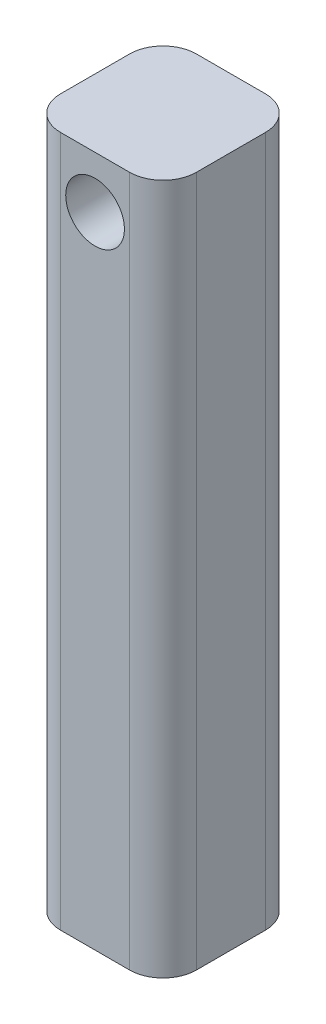
SolidWorks part; units mm, degrees
ref_plane "Front Plane" through (0, 0, 0) normal (0, 0, 1) x (1, 0, 0)
ref_plane "Top Plane" through (0, 0, 0) normal (0, 1, 0) x (1, 0, 0)
ref_plane "Right Plane" through (0, 0, 0) normal (1, 0, 0) x (0, 0, -1)
sketch "Sketch1" plane through (0, 0, 0) normal (0, 1, 0) x (1, 0, 0)
  line L1 (-3, -5.9) -> (3, -5.9)
  line L2 (-5.9, -3) -> (-5.9, 3)
  line L3 (-3, 5.9) -> (3, 5.9)
  line L4 (5.9, -3) -> (5.9, 3)
  line L5 (-5.9, -5.9) -> (5.9, 5.9) construction
  line L6 (-5.9, 5.9) -> (5.9, -5.9) construction
  arc A0 (3, -5.9) -> (5.9, -3) centre (3, -3) ccw
  arc A1 (-3, -5.9) -> (-5.9, -3) centre (-3, -3) cw
  arc A2 (-5.9, 3) -> (-3, 5.9) centre (-3, 3) cw
  arc A3 (3, 5.9) -> (5.9, 3) centre (3, 3) cw
  circle A4 centre (0, 0) radius 2.55
  point P0 (0, 0)
  dimension "D2" = 2.9
  dimension "D3" = 2.9
  dimension "D4" = 5.1
  dimension "D1" = 11.8
extrude "Boss-Extrude1" add sketch "Sketch1" along normal blind 52
sketch "Sketch2" plane through (0, 52, 0) normal (0, 1, 0) x (1, 0, 0)
  line L4 (5.9, -3) -> (5.9, 3)
  line L5 (3, 5.9) -> (-3, 5.9)
  line L6 (-5.9, 3) -> (-5.9, -3)
  line L7 (-3, -5.9) -> (3, -5.9)
  line L8 (5.9, -3) -> (5.9, 3)
  line L9 (3, 5.9) -> (-3, 5.9)
  line L10 (-5.9, 3) -> (-5.9, -3)
  line L11 (-3, -5.9) -> (3, -5.9)
  arc A4 (3, -5.9) -> (5.9, -3) centre (3, -3) ccw
  arc A5 (5.9, 3) -> (3, 5.9) centre (3, 3) ccw
  arc A6 (-3, 5.9) -> (-5.9, 3) centre (-3, 3) ccw
  arc A7 (-5.9, -3) -> (-3, -5.9) centre (-3, -3) ccw
  arc A8 (3, -5.9) -> (5.9, -3) centre (3, -3) ccw
  arc A9 (5.9, 3) -> (3, 5.9) centre (3, 3) ccw
  arc A10 (-3, 5.9) -> (-5.9, 3) centre (-3, 3) ccw
  arc A11 (-5.9, -3) -> (-3, -5.9) centre (-3, -3) ccw
  dimension "D1" = 0
extrude "Boss-Extrude2" add sketch "Sketch2" along normal blind 8
ref_plane "Plane1" through (0, 3, 0) normal (0, -1, 0) x (-1, 0, 0)
sketch "Sketch3" plane through (0, 3, 0) normal (0, -1, 0) x (-1, 0, 0)
  line L0 (2.7424, 4.75) -> (6.3053, 4.75)
  line L1 (-2.7424, 4.75) -> (-5.4848, 0)
  line L2 (-5.4848, 0) -> (-2.7424, -4.75)
  line L3 (-2.7424, -4.75) -> (2.7424, -4.75)
  line L4 (2.7424, -4.75) -> (5.4848, 0) construction
  line L5 (5.4848, 0) -> (2.7424, 4.75) construction
  line L6 (2.7424, 4.75) -> (-2.7424, 4.75)
  line L7 (6.3053, 4.75) -> (6.3053, -4.75)
  line L8 (6.3053, -4.75) -> (2.7424, -4.75)
  circle A0 centre (0, 0) radius 4.75 construction
  dimension "D1" = 9.5
extrude "Cut-Extrude1" cut sketch "Sketch3" against normal mid plane 3.05
sketch "Sketch4" plane through (0, 0, -5.9) normal (0, 0, -1) x (-1, 0, 0)
  line L0 (-3, 60) -> (3, 60) construction
  circle A0 centre (0, 55.5) radius 2.55
  dimension "D1" = 5.1
  dimension "D2" = 4.5
extrude "Cut-Extrude2" cut sketch "Sketch4" against normal through all
